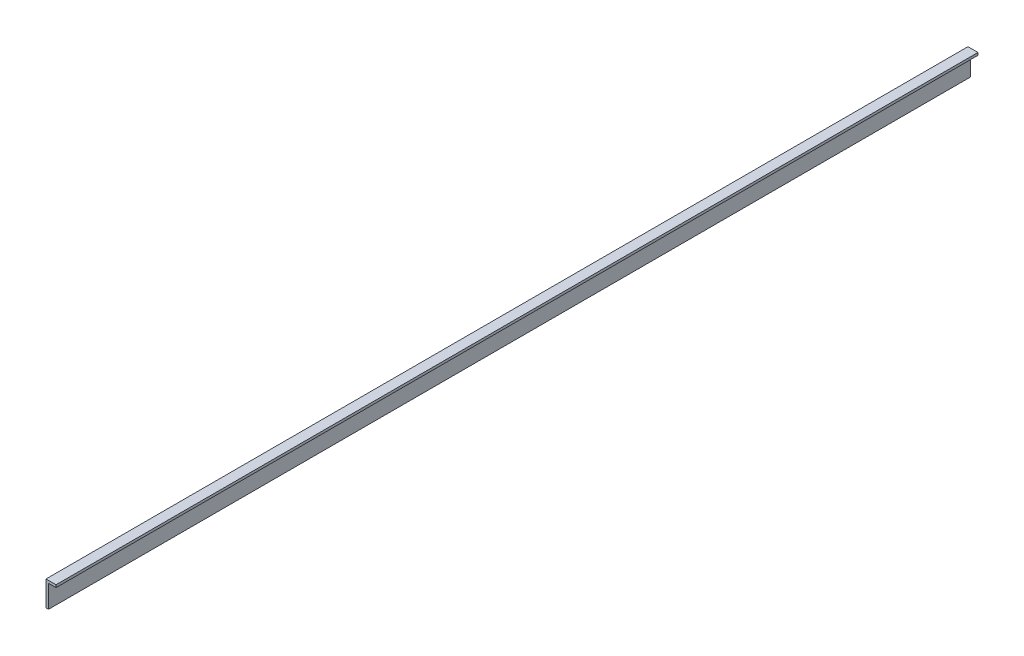
SolidWorks part; units mm, degrees
ref_plane "Front Plane" through (0, 0, 0) normal (0, 0, 1) x (1, 0, 0)
ref_plane "Top Plane" through (0, 0, 0) normal (0, 1, 0) x (1, 0, 0)
ref_plane "Right Plane" through (0, 0, 0) normal (1, 0, 0) x (0, 0, -1)
other "Configuration Table"
sketch "Sketch1" plane through (0, 0, 0) normal (0, 0, 1) x (1, 0, 0)
  line L0 (541.5, 404.5) -> (539.5, 404.5)
  line L1 (539.5, 404.5) -> (539.5, 424.5)
  line L2 (539.5, 424.5) -> (547.5, 424.5)
  line L3 (547.5, 424.5) -> (547.5, 422.5)
  line L4 (547.5, 422.5) -> (541.5, 422.5)
  line L5 (541.5, 422.5) -> (541.5, 404.5)
extrude "STORE_kaset_L_raf_4_sol_1" add sketch "Sketch1" against normal blind 735.5 from offset 20 separate body
